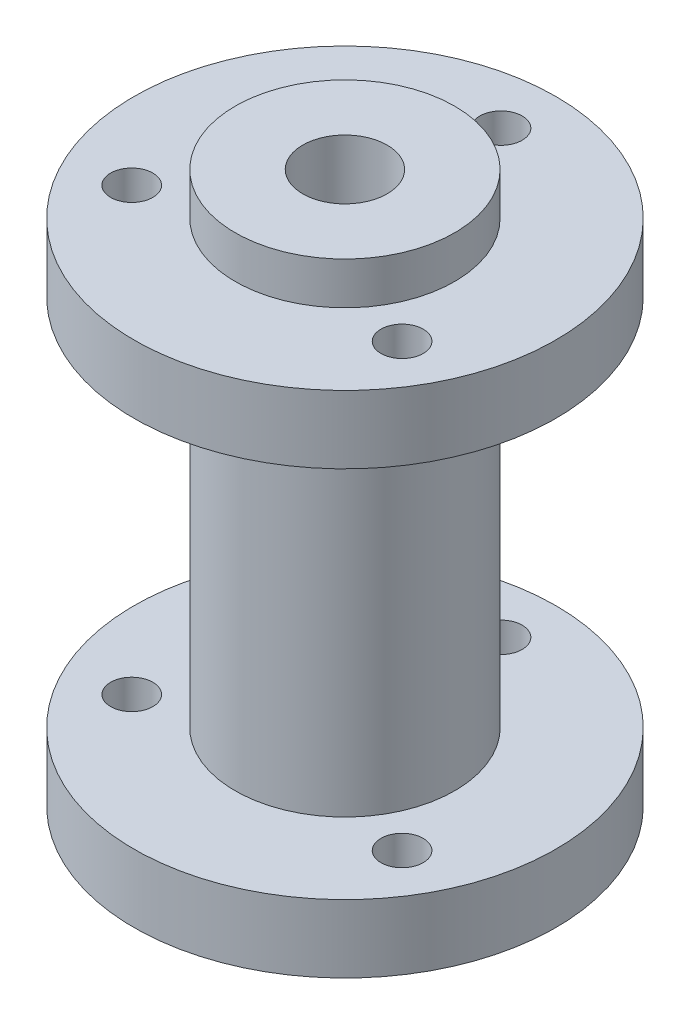
SolidWorks part; units mm, degrees
ref_plane "Piano frontale" through (0, 0, 0) normal (0, 0, 1) x (1, 0, 0)
ref_plane "Piano superiore" through (0, 0, 0) normal (0, 1, 0) x (1, 0, 0)
ref_plane "Piano destro" through (0, 0, 0) normal (1, 0, 0) x (0, 0, -1)
sketch "Schizzo1" plane through (0, 0, 0) normal (0, 0, 1) x (1, 0, 0)
  line L0 (0, 0) -> (0, 72.7755) construction
  line L1 (2.5, -12.56) -> (4.5, -12.56)
  line L2 (2.5, -17.56) -> (2.5, -12.56)
  line L3 (6.495, -17.56) -> (2.5, -17.56)
  line L4 (6.495, -15.06) -> (6.495, -17.56)
  line L5 (6.5, -11.04) -> (6.5, 11.04)
  line L6 (6.5, 11.04) -> (12.485, 11.04)
  line L7 (12.485, 11.04) -> (12.485, 15.06)
  line L8 (12.485, 15.06) -> (6.495, 15.06)
  line L9 (6.495, 15.06) -> (6.495, 17.56)
  line L10 (6.495, 17.56) -> (2.5, 17.56)
  line L11 (2.5, 12.56) -> (2.5, 17.56)
  line L12 (2.5, 12.56) -> (4.5, 12.56)
  line L13 (4.5, 12.56) -> (4.5, -12.56)
  line L14 (4.5, 0) -> (6.5, 0) construction
  line L15 (12.485, -15.06) -> (6.495, -15.06)
  line L16 (12.485, -11.04) -> (12.485, -15.06)
  line L17 (6.5, -11.04) -> (12.485, -11.04)
  dimension "D1" = 13
  dimension "D2" = 24.97
  dimension "D3" = 12.99
  dimension "D4" = 2.5
  dimension "D5" = 2
  dimension "D6" = 5
  dimension "D7" = 22.08
  dimension "D8" = 35.12
  dimension "D9" = 5
revolve "Rivoluzione1" add sketch "Schizzo1" angle 360 about L0
hole_wizard "Foro filettato M3x0.5-1" positions "Schizzo3" profile "Schizzo2" tap size "M3x0.5" standard "Ansi Metric" end condition through all
sketch "Schizzo3" plane through (0, 15.06, 0) normal (0, 1, 0) x (1, 0, 0)
  line L0 (-8, -4.6188) -> (8, -4.6188) construction
  line L1 (8, -4.6188) -> (0, 9.2376) construction
  line L2 (0, 9.2376) -> (-8, -4.6188) construction
  circle A0 centre (0, 0) radius 9.2376 construction
  point P37 (0, 9.2376)
  point P39 (8, -4.6188)
  point P41 (-8, -4.6188)
  dimension "D1" = 16
sketch "Schizzo2" plane through (0, 15.06, -9.2376) normal (1, 0, 0) x (0, 0, 1)
  line L0 (0, 0) -> (0, 32.62)
  line L1 (0, 32.62) -> (1.25, 32.62)
  line L2 (1.25, 32.62) -> (1.25, 0)
  line L5 (1.25, 0) -> (0, 0)
  line L11 (0, -6.35) -> (0, 107.95) construction
  dimension "Thread Major Dia." = 2.5
  dimension "Thru Tap Drill Depth" = 32.62
